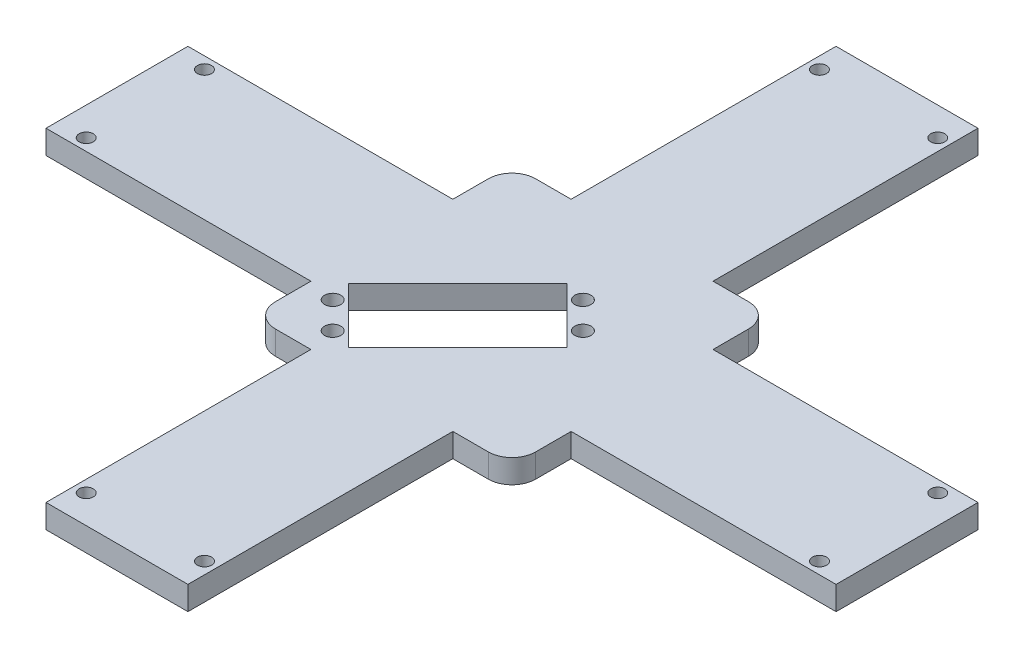
SolidWorks part; units mm, degrees
ref_plane "Plan de face" through (0, 0, 0) normal (0, 0, 1) x (1, 0, 0)
ref_plane "Plan de dessus" through (0, 0, 0) normal (0, 1, 0) x (1, 0, 0)
ref_plane "Plan de droite" through (0, 0, 0) normal (1, 0, 0) x (0, 0, -1)
sketch "Esquisse1" plane through (0, 0, 0) normal (0, 1, 0) x (1, 0, 0)
  line L0 (19.05, 106.045) -> (-19.05, 106.045)
  line L2 (34.925, 19.05) -> (106.0555, 19.05)
  line L5 (19.05, -34.925) -> (19.05, -106.045)
  line L6 (19.05, -106.045) -> (-19.05, -106.045)
  line L7 (-19.05, -106.045) -> (-19.05, -34.925)
  line L8 (-34.925, -19.05) -> (-106.045, -19.05)
  line L9 (-106.045, -19.05) -> (-106.045, 19.05)
  line L10 (-106.045, 19.05) -> (-34.925, 19.05)
  line L12 (-28.575, 34.925) -> (28.575, 34.925) construction
  line L13 (19.05, 34.925) -> (19.05, 106.045)
  line L14 (-19.05, 106.045) -> (-19.05, 34.925)
  line L15 (-28.575, 34.925) -> (-19.05, 34.925)
  line L16 (-111.125, -19.05) -> (-34.925, -19.05) construction
  line L17 (-19.05, 111.125) -> (-19.05, 34.925) construction
  line L18 (19.05, 111.125) -> (19.05, 34.925) construction
  line L19 (19.05, -106.045) -> (80.645, -106.045) construction
  line L20 (19.05, -111.125) -> (19.05, -34.925) construction
  line L21 (-19.05, -111.125) -> (-19.05, -34.925) construction
  line L22 (-111.125, 19.05) -> (-34.925, 19.05) construction
  line L23 (19.05, 34.925) -> (28.575, 34.925)
  line L24 (34.925, 28.575) -> (34.925, 19.05)
  line L25 (34.925, -19.05) -> (34.925, -28.575)
  line L26 (28.575, -34.925) -> (19.05, -34.925)
  line L27 (-34.925, -19.05) -> (-34.925, -28.575)
  line L28 (-28.575, -34.925) -> (-19.05, -34.925)
  line L29 (-34.925, 19.05) -> (-34.925, 28.575)
  line L32 (34.925, -19.05) -> (106.0555, -19.05)
  line L33 (106.0555, -19.05) -> (106.0555, 19.05)
  line L34 (111.125, 16.6688) -> (111.125, -16.6687) construction
  line L35 (6.2781, 111.125) -> (-6.2781, 111.125) construction
  line L36 (-111.125, -16.6688) -> (-111.125, 16.6687) construction
  arc A0 (28.575, 34.925) -> (34.925, 28.575) centre (28.575, 28.575) cw
  arc A1 (28.575, -34.925) -> (34.925, -28.575) centre (28.575, -28.575) ccw construction
  arc A2 (34.925, -28.575) -> (28.575, -34.925) centre (28.575, -28.575) cw
  arc A3 (-34.925, -28.575) -> (-28.575, -34.925) centre (-28.575, -28.575) ccw
  arc A4 (-34.925, 28.575) -> (-28.575, 34.925) centre (-28.575, 28.575) cw
  dimension "D1" = 5.0695
  dimension "D2" = 5.08
  dimension "D3" = 5.08
extrude "Boss.-Extru.1" add sketch "Esquisse1" along normal blind 6.35
sketch "Esquisse2" plane through (0, 0, 0) normal (0, -1, 0) x (1, 0, 0)
  circle A0 centre (-20.475, 27.6592) radius 2.1844
  circle A1 centre (-27.6592, 20.475) radius 2.1844
  circle A2 centre (13.1112, -5.927) radius 2.1844
  circle A3 centre (5.927, -13.1112) radius 2.1844
  arc A4 (-22.6551, 27.796) -> (-20.6118, 29.8393) centre (-20.475, 27.6592) ccw construction
  arc A5 (-29.8393, 20.6118) -> (-27.796, 22.6551) centre (-27.6592, 20.475) ccw construction
  arc A6 (8.1071, -13.248) -> (6.0638, -15.2913) centre (5.927, -13.1112) ccw construction
  arc A7 (15.2913, -6.0638) -> (13.248, -8.1071) centre (13.1112, -5.927) ccw construction
extrude "Enlèv. mat.-Extru.1" cut sketch "Esquisse2" against normal up to next
sketch "Esquisse3" plane through (0, 0, 0) normal (0, -1, 0) x (1, 0, 0)
  line L0 (2.0514, -9.8025) -> (9.8025, -2.0514) construction
  line L1 (16.6524, -6.8758) -> (15.7036, -3.3346)
  line L2 (15.7036, -3.3346) -> (12.1623, -2.3857)
  line L3 (12.1623, -2.3857) -> (9.5699, -4.9781)
  line L4 (9.5699, -4.9781) -> (10.5188, -8.5193)
  line L5 (10.5188, -8.5193) -> (14.06, -9.4682)
  line L6 (14.06, -9.4682) -> (16.6524, -6.8758)
  line L7 (9.4682, -14.06) -> (8.5193, -10.5188)
  line L8 (8.5193, -10.5188) -> (4.9781, -9.5699)
  line L9 (4.9781, -9.5699) -> (2.3857, -12.1623)
  line L10 (2.3857, -12.1623) -> (3.3346, -15.7036)
  line L11 (3.3346, -15.7036) -> (6.8758, -16.6524)
  line L12 (6.8758, -16.6524) -> (9.4682, -14.06)
  line L13 (-17.8826, 30.2516) -> (-21.4239, 31.2004)
  line L14 (-21.4239, 31.2004) -> (-24.0162, 28.6081)
  line L15 (-24.0162, 28.6081) -> (-23.0674, 25.0668)
  line L16 (-23.0674, 25.0668) -> (-19.5261, 24.1179)
  line L17 (-19.5261, 24.1179) -> (-16.9337, 26.7103)
  line L18 (-16.9337, 26.7103) -> (-17.8826, 30.2516)
  line L19 (-28.6081, 24.0162) -> (-31.2004, 21.4239)
  line L20 (-31.2004, 21.4239) -> (-30.2516, 17.8826)
  line L21 (-30.2516, 17.8826) -> (-26.7103, 16.9337)
  line L22 (-26.7103, 16.9337) -> (-24.1179, 19.5261)
  line L23 (-24.1179, 19.5261) -> (-25.0668, 23.0674)
  line L24 (-25.0668, 23.0674) -> (-28.6081, 24.0162)
  line L25 (10.3575, -3.2925) -> (8.85, -4.7999) construction
  circle A0 centre (13.1112, -5.927) radius 3.175 construction
  circle A1 centre (5.927, -13.1112) radius 3.175 construction
  circle A2 centre (-20.475, 27.6592) radius 3.175 construction
  circle A3 centre (-27.6592, 20.475) radius 3.175 construction
  dimension "D1" = 0.635
extrude "Enlèv. mat.-Extru.2" cut sketch "Esquisse3" against normal blind 2.54
sketch "Esquisse4" plane through (0, 0, 0) normal (0, -1, 0) x (1, 0, 0)
  line L0 (-29.4193, 14.5121) -> (-14.5121, 29.4193)
  line L1 (-14.5121, 29.4193) -> (14.8174, 0.0898)
  line L2 (14.8174, 0.0898) -> (-0.0898, -14.8174)
  line L3 (-0.0898, -14.8174) -> (-29.4193, 14.5121)
  line L4 (-29.4193, 14.5121) -> (-14.5121, 29.4193) construction
  line L5 (14.8174, 0.0898) -> (-0.0898, -14.8174) construction
  line L6 (14.8174, 0.0898) -> (-14.5121, 29.4193) construction
extrude "Enlèv. mat.-Extru.3" cut sketch "Esquisse4" against normal up to next
sketch "Esquisse5" plane through (0, 6.35, 0) normal (0, 1, 0) x (1, 0, 0)
  circle A0 centre (15.875, -98.425) radius 1.8986
  circle A1 centre (-15.875, -98.425) radius 1.8986
  circle A2 centre (15.875, -98.425) radius 1.8987 construction
  circle A3 centre (-15.875, -98.425) radius 1.8987 construction
extrude "Enlèv. mat.-Extru.4" cut sketch "Esquisse5" against normal through all
pattern_circular "Répétition circulaire1" count 4 over 360 about axis through (0, 0, 0) along (0, 1, 0) of "Enlèv. mat.-Extru.4"
